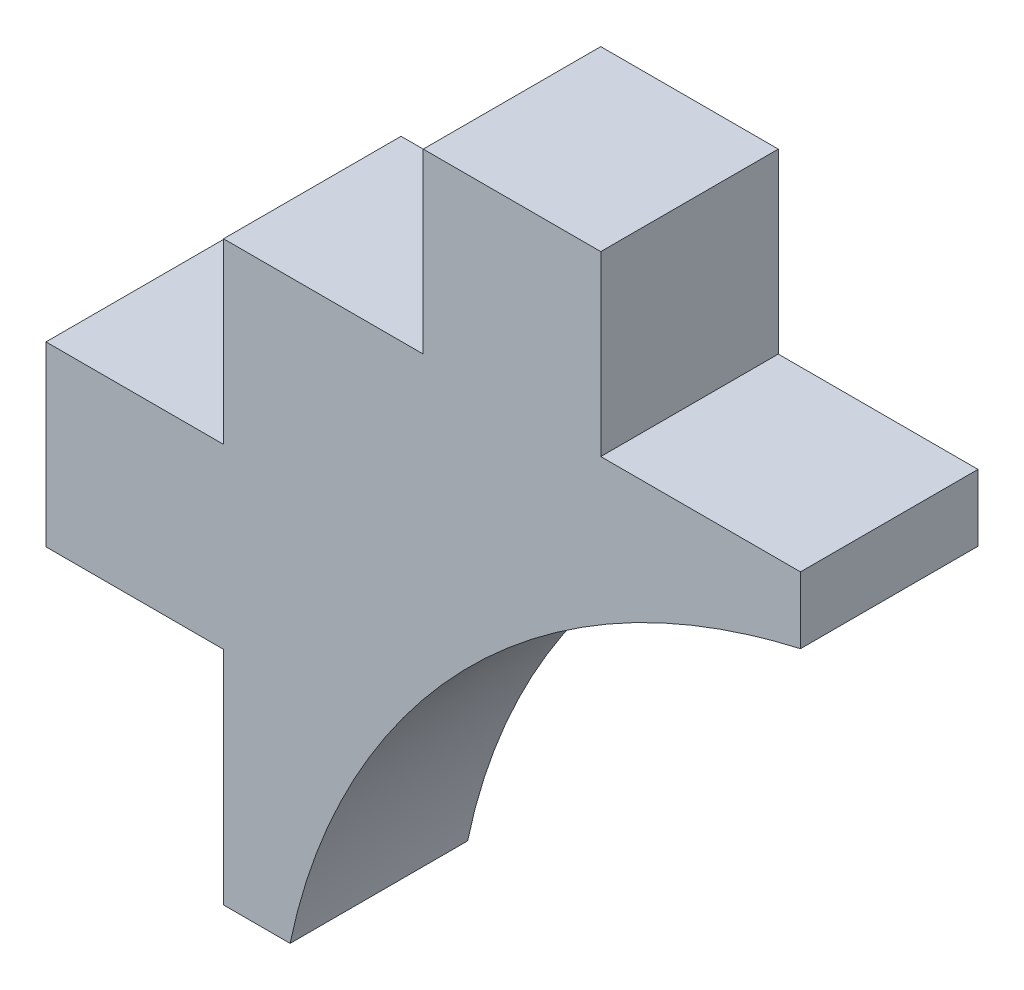
SolidWorks part; units mm, degrees
ref_plane "Front Plane" through (0, 0, 0) normal (0, 0, 1) x (1, 0, 0)
ref_plane "Top Plane" through (0, 0, 0) normal (0, 1, 0) x (1, 0, 0)
ref_plane "Right Plane" through (0, 0, 0) normal (1, 0, 0) x (0, 0, -1)
sketch "Sketch1" plane through (0, 0, 0) normal (0, 0, 1) x (1, 0, 0)
  line L1 (0, 13) -> (4.5, 13)
  line L2 (4.5, 13) -> (4.5, 17)
  line L3 (4.5, 17) -> (8.5, 17)
  line L4 (8.5, 17) -> (8.5, 13)
  line L5 (8.5, 13) -> (13, 13)
  line L6 (13, 13) -> (13, 11.5)
  line L8 (0, 0) -> (1.5, 0)
  line L9 (0, 13) -> (0, 8.9879)
  line L14 (0, 8.9879) -> (-4, 8.9879)
  line L16 (0, 4.9879) -> (-4, 4.9879)
  line L17 (-4, 8.9879) -> (-4, 4.9879)
  line L18 (0, 4.9879) -> (0, 0)
  spline S0 degree 3 poles (1.5, 0) (2.5204, 4.9504) (6.474, 10.017) (13, 11.5) knots 0 0 0 0 1 1 1 1
  dimension "D1" = 4
  dimension "D2" = 4.5
  dimension "D3" = 4.5
  dimension "D4" = 4
  dimension "D5" = 4
  dimension "D6" = 1.5
  dimension "D7" = 4
extrude "Boss-Extrude1" add sketch "Sketch1" along normal blind 4
